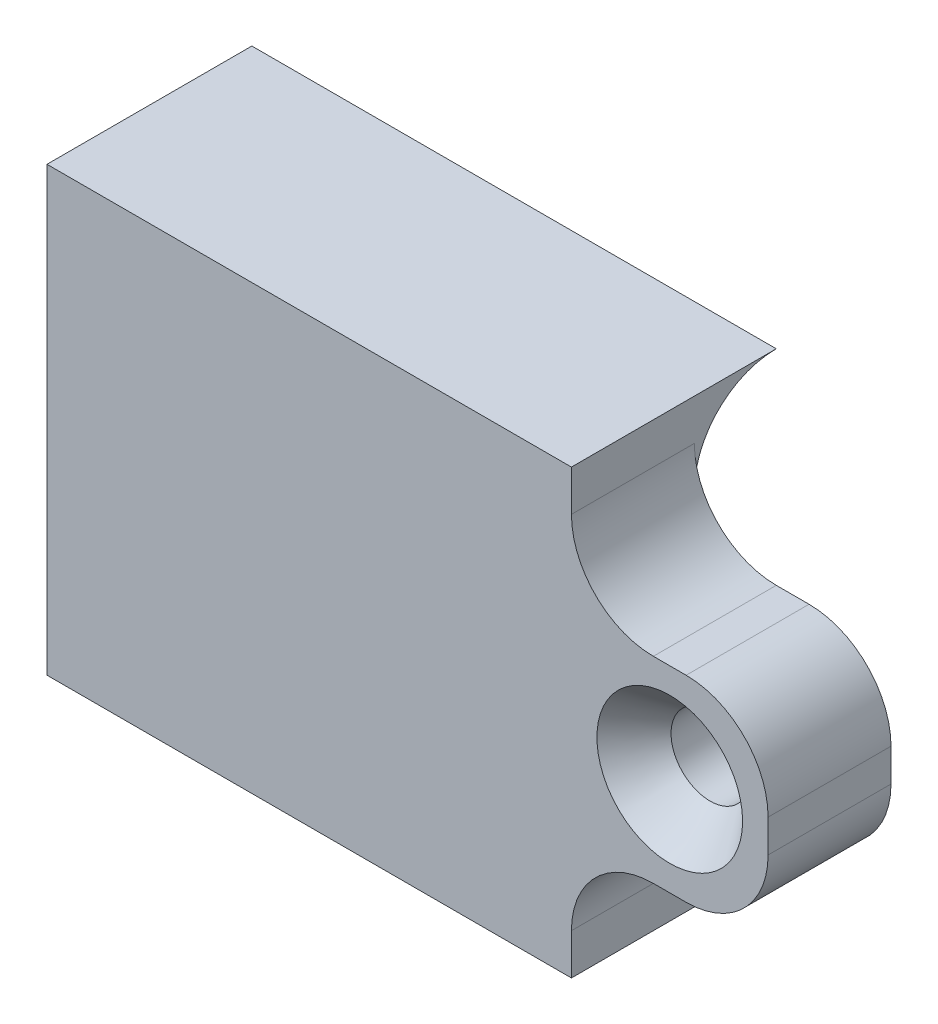
SolidWorks part; units mm, degrees
material "ABS"
ref_plane "Front" through (0, 0, 0) normal (0, 0, 1) x (1, 0, 0)
ref_plane "Top" through (0, 0, 0) normal (0, 1, 0) x (1, 0, 0)
ref_plane "Right" through (0, 0, 0) normal (1, 0, 0) x (0, 0, -1)
sketch "Sketch1" plane through (0, 0, 0) normal (0, 0, 1) x (1, 0, 0)
  line L1 (-6.4, 5.4) -> (6.4, 5.4)
  line L2 (-6.4, 5.4) -> (-6.4, -5.4)
  line L3 (-6.4, -5.4) -> (6.4, -5.4)
  line L4 (6.4, 5.4) -> (6.4, -5.4)
  line L5 (-6.4, 5.4) -> (6.4, -5.4) construction
  line L6 (-6.4, -5.4) -> (6.4, 5.4) construction
  line L7 (6.4, 2.4) -> (11.2, 2.4)
  line L8 (6.4, 2.4) -> (6.4, -2.4)
  line L9 (6.4, -2.4) -> (11.2, -2.4)
  line L10 (11.2, 2.4) -> (11.2, -2.4)
  point P0 (0, 0)
  point P10 (6.4, 0)
  dimension "D1" = 12.8
  dimension "D2" = 10.8
  dimension "D3" = 4.8
extrude "Boss-Extrude1" add sketch "Sketch1" along normal mid plane 3 contours L4 L1 L2 L3 | L10 L7 L4 L9
hole_wizard "#2 Clearance Hole1" positions "Sketch3" profile "Sketch2" hole size "#2" standard "ANSI Inch" end condition up to next
sketch "Sketch3" plane through (0, 0, 1.5) normal (0, 0, 1) x (1, 0, 0)
  line L0 (6.4, 2.4) -> (11.2, -2.4) construction
  point P0 (8.8, 0)
sketch "Sketch2" plane through (8.8, 0, 1.5) normal (1, 0, 0) x (0, -1, 0)
  line L0 (0, 0) -> (0, 3)
  line L1 (0, 3) -> (0.9525, 3)
  line L2 (0.9525, 3) -> (0.9525, 0.9838)
  line L3 (0.9525, 0.9838) -> (1.778, 0)
  line L5 (1.778, 0) -> (0, 0)
  line L6 (-0.9525, 0.9838) -> (-1.778, 0) construction
  line L11 (0, -6.35) -> (0, 107.95) construction
  dimension "Thru Hole Dia." = 1.905
  dimension "Thru Hole Depth" = 3
  dimension "Near C'Sink Dia." = 3.556
  dimension "Near C'Sink Angle" = 80
fillet "Fillet1" radius 2 4 edges at (11.2, -2.4, 0) (6.4, -2.4, 0) (11.2, 2.4, 0) (6.4, 2.4, 0)
sketch "Sketch4" plane through (0, 0, 0) normal (1, 0, 0) x (0, 0, -1)
  line L6 (1.5, 5.4) -> (3.5, 5.4)
  line L7 (1.5, 5.4) -> (1.5, 3.4)
  line L8 (1.5, 2.4) -> (1.5, 4.4) construction
  line L9 (50, 0) -> (-50, 0) construction
  line L10 (1.5, -5.4) -> (1.5, -3.4)
  line L11 (1.5, -5.4) -> (3.5, -5.4)
  arc A2 (1.5, 3.4) -> (3.5, 5.4) centre (3.5, 3.4) cw
  arc A3 (1.5, -3.4) -> (3.5, -5.4) centre (3.5, -3.4) ccw
  dimension "D1" = 2
extrude "Boss-Extrude2" add sketch "Sketch4" against normal up to surface and the other way up to surface up to face at (-6.4, 0, 0) other way up to face at (6.4, 4.9, 0)
